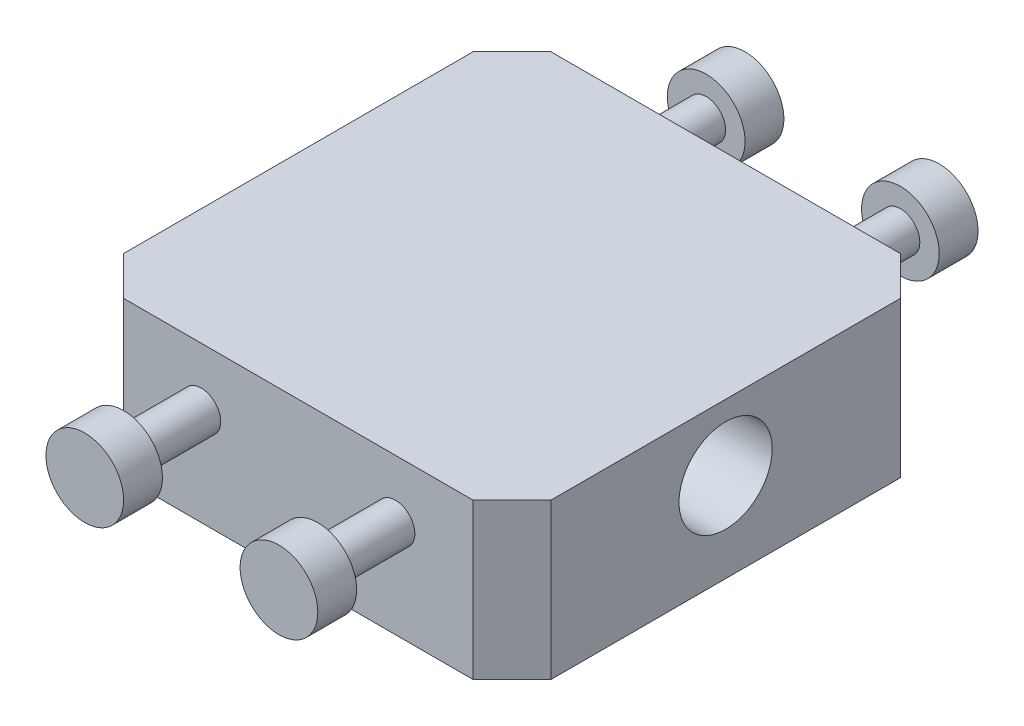
SolidWorks part; units mm, degrees
ref_plane "Front Plane" through (0, 0, 0) normal (0, 0, 1) x (1, 0, 0)
ref_plane "Top Plane" through (0, 0, 0) normal (0, 1, 0) x (1, 0, 0)
ref_plane "Right Plane" through (0, 0, 0) normal (1, 0, 0) x (0, 0, -1)
sketch "Sketch2" plane through (0, 0, 0) normal (0, 1, 0) x (1, 0, 0)
  line L1 (0, 0) -> (110, 0)
  line L2 (0, 0) -> (0, 110)
  line L3 (0, 110) -> (110, 110)
  line L4 (110, 0) -> (110, 110)
  dimension "D1" = 110
  dimension "D2" = 110
extrude "Boss-Extrude1" add sketch "Sketch2" along normal blind 30
chamfer "Chamfer1" distance 10 angle 45 4 edges at (0, 15, -110) (110, 15, -110) (110, 15, 0) (0, 15, 0)
sketch "Sketch3" plane through (0, 0, 0) normal (0, 0, 1) x (1, 0, 0)
  line L0 (100, 0) -> (100, 30) construction
  line L1 (10, 30) -> (10, 0) construction
  line L2 (10, 30) -> (100, 30) construction
  circle A0 centre (30, 20) radius 5
  circle A1 centre (80, 20) radius 5
  dimension "D1" = 10
  dimension "D2" = 10
  dimension "D3" = 20
  dimension "D4" = 20
  dimension "D5" = 10
  dimension "D6" = 10
extrude "Boss-Extrude2" add sketch "Sketch3" along normal blind 20
sketch "Sketch4" plane through (0, 0, -110) normal (0, 0, -1) x (-1, 0, 0)
  line L2 (-100, 30) -> (-10, 30) construction
  line L3 (-100, 30) -> (-100, 0) construction
  line L5 (-10, 0) -> (-10, 30) construction
  circle A0 centre (-80, 20) radius 5
  circle A1 centre (-30, 20) radius 5
  dimension "D5" = 10
  dimension "D6" = 10
  dimension "D1" = 20
  dimension "D2" = 20
  dimension "D3" = 10
  dimension "D4" = 10
extrude "Boss-Extrude3" add sketch "Sketch4" along normal blind 20
sketch "Sketch5" plane through (0, 0, -130) normal (0, 0, -1) x (-1, 0, 0)
  circle A0 centre (-80, 20) radius 10
  circle A1 centre (-30, 20) radius 10
  dimension "D1" = 20
  dimension "D2" = 20
extrude "Boss-Extrude4" add sketch "Sketch5" along normal blind 10
sketch "Sketch6" plane through (0, 0, 20) normal (0, 0, 1) x (1, 0, 0)
  circle A0 centre (30, 20) radius 10
  circle A1 centre (80, 20) radius 10
  dimension "D1" = 20
  dimension "D2" = 20
extrude "Boss-Extrude5" add sketch "Sketch6" along normal blind 10
sketch "Sketch9" plane through (0, 30, 0) normal (0, 1, 0) x (1, 0, 0)
  line L0 (10, 110) -> (100, 110)
  line L1 (100, 110) -> (110, 100)
  line L2 (110, 100) -> (110, 10)
  line L3 (110, 10) -> (100, 0)
  line L4 (100, 0) -> (10, 0)
  line L5 (10, 0) -> (0, 10)
  line L6 (0, 10) -> (0, 100)
  line L7 (0, 100) -> (10, 110)
extrude "Boss-Extrude6" add sketch "Sketch9" along normal blind 5
sketch "Sketch10" plane through (0, 0, 0) normal (0, -1, 0) x (1, 0, 0)
  line L0 (10, 0) -> (100, 0)
  line L1 (100, 0) -> (110, -10)
  line L2 (110, -10) -> (110, -100)
  line L3 (110, -100) -> (100, -110)
  line L4 (100, -110) -> (10, -110)
  line L5 (10, -110) -> (0, -100)
  line L6 (0, -100) -> (0, -10)
  line L7 (0, -10) -> (10, 0)
extrude "Boss-Extrude7" add sketch "Sketch10" along normal blind 5
sketch "Sketch11" plane through (110, 0, 0) normal (1, 0, 0) x (0, 0, -1)
sketch "Sketch12" plane through (110, 0, 0) normal (1, 0, 0) x (0, 0, -1)
sketch "Sketch15" plane through (110, 0, 0) normal (1, 0, 0) x (0, 0, -1)
  circle A0 centre (55, 18) radius 12
extrude "Cut-Extrude1" cut sketch "Sketch15" against normal blind 200
